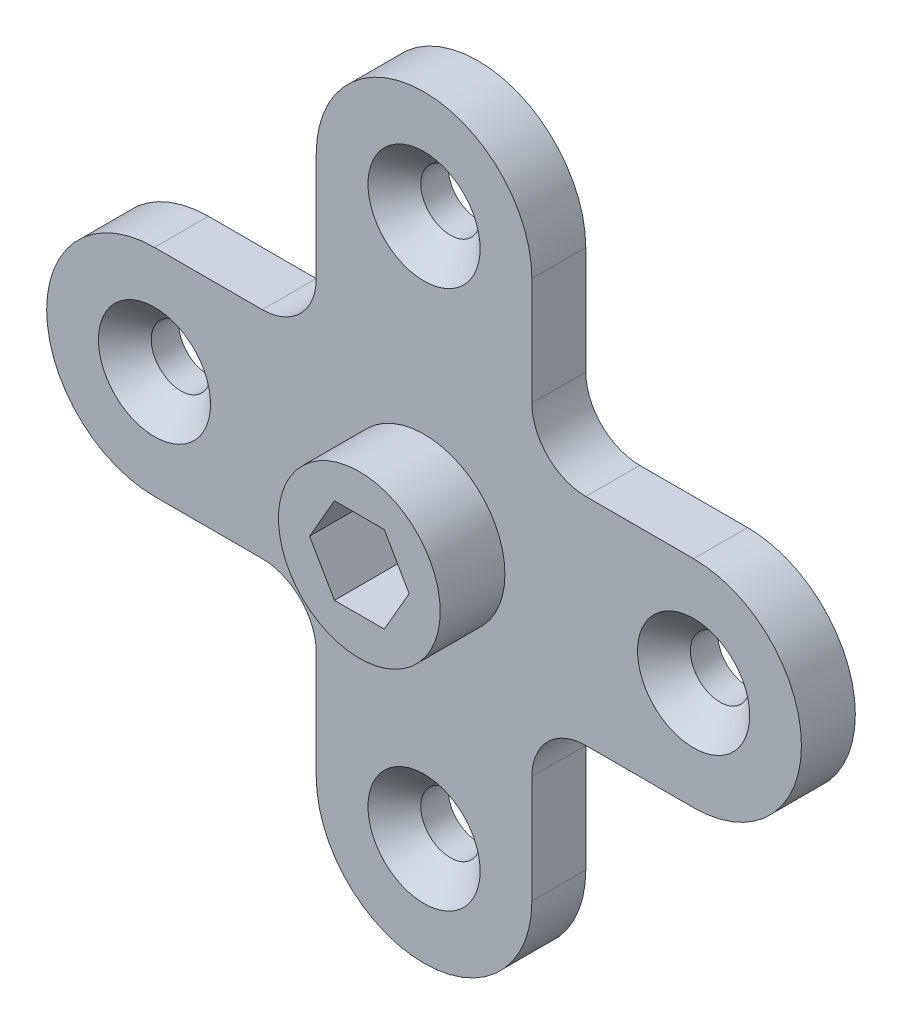
SolidWorks part; units mm, degrees
ref_plane "前基準面" through (0, 0, 0) normal (0, 0, 1) x (1, 0, 0)
ref_plane "上基準面" through (0, 0, 0) normal (0, 1, 0) x (1, 0, 0)
ref_plane "右基準面" through (0, 0, 0) normal (1, 0, 0) x (0, 0, -1)
sketch "草圖1" plane through (0, 0, 0) normal (0, 0, 1) x (1, 0, 0)
  line L0 (-25, 0) -> (25, 0) construction
  line L1 (0, 25) -> (0, -25) construction
  line L2 (0, 25) -> (0, -25) construction
  line L3 (10, 25) -> (10, 10)
  line L4 (-10, 25) -> (-10, 10)
  line L5 (-25, 0) -> (25, 0) construction
  line L6 (-25, 10) -> (-10, 10)
  line L7 (-25, -10) -> (-10, -10)
  line L8 (-10, -10) -> (-10, -25)
  line L9 (10, -10) -> (10, -25)
  line L10 (10, -10) -> (25, -10)
  line L11 (10, 10) -> (25, 10)
  arc A0 (10, 25) -> (-10, 25) centre (0, 25) ccw
  arc A1 (-10, -25) -> (10, -25) centre (0, -25) ccw
  arc A2 (-25, 10) -> (-25, -10) centre (-25, 0) ccw
  arc A3 (25, -10) -> (25, 10) centre (25, 0) ccw
  circle A4 centre (-25, 0) radius 2.5 construction
  circle A5 centre (25, 0) radius 2.5 construction
  circle A6 centre (0, 25) radius 2.5 construction
  circle A7 centre (0, -25) radius 2.5 construction
  point P4 (0, 0)
  point P6 (0, 0)
  point P7 (0, 0)
  point P12 (0, 0)
  point P26 (0, 25)
  point P27 (-25, 0)
  point P28 (0, -25)
  point P29 (25, 0)
  dimension "D3" = 10
  dimension "D4" = 10
  dimension "D5" = 5
  dimension "D1" = 50
  dimension "D2" = 50
extrude "填料-伸長1" add sketch "草圖1" along normal mid plane 5
sketch "草圖2" plane through (0, 0, 2.5) normal (0, 0, 1) x (1, 0, 0)
  point P0 (0, 25)
  point P1 (-25, 0)
  point P3 (0, -25)
  point P5 (25, 0)
hole_wizard "M5 錐坑平頭螺釘的錐孔1" positions "3D草圖2" profile "草圖6" countersink size "M5" standard "ISO" end condition through all
sketch3d "3D草圖2"
  point P0 (0, 25, 2.5)
  point P3 (0, -25, 2.5)
  point P6 (25, 0, 2.5)
  point P9 (-25, 0, 2.5)
sketch "草圖6" plane through (0, 25, 2.5) normal (1, 0, 0) x (0, -1, 0)
  line L0 (0, 0) -> (0, 5)
  line L1 (0, 5) -> (2.75, 5)
  line L2 (2.75, 5) -> (2.75, 2.45)
  line L3 (2.75, 2.45) -> (5.2, 0)
  line L5 (5.2, 0) -> (0, 0)
  line L6 (-2.75, 2.45) -> (-5.2, 0) construction
  line L11 (0, -6.35) -> (0, 107.95) construction
  dimension "貫穿孔直徑" = 5.5
  dimension "貫穿孔深度" = 5
  dimension "近端錐孔直徑" = 10.4
  dimension "近端錐孔角度" = 90
fillet "圓角1" radius 5 4 edges at (-10, -10, 0) (-10, 10, 0) (10, 10, 0) (10, -10, 0)
sketch "草圖10" plane through (0, 0, -2.5) normal (0, 0, -1) x (-1, 0, 0)
  line L0 (0, 0) -> (0, 9.7359) construction
  line L1 (0, 9.7359) -> (8.944, 0) construction
  line L2 (8.944, 0) -> (-5.6831, 0) construction
  point P6 (0, 0)
hole_wizard "M5 錐坑平頭螺釘的錐孔3" positions "3D草圖7" profile "草圖13" countersink size "M5" standard "ISO" end condition through all
sketch3d "3D草圖7"
  point P0 (0, 0, -2.5)
sketch "草圖13" plane through (0, 0, -2.5) normal (1, 0, 0) x (0, 1, 0)
  line L0 (0, 0) -> (0, 5)
  line L1 (0, 5) -> (2.75, 5)
  line L2 (2.75, 5) -> (2.75, 2.45)
  line L3 (2.75, 2.45) -> (5.2, 0)
  line L5 (5.2, 0) -> (0, 0)
  line L6 (-2.75, 2.45) -> (-5.2, 0) construction
  line L11 (0, -6.35) -> (0, 107.95) construction
  dimension "貫穿孔直徑" = 5.5
  dimension "貫穿孔深度" = 5
  dimension "近端錐孔直徑" = 10.4
  dimension "近端錐孔角度" = 90
sketch "草圖14" plane through (0, 0, 2.5) normal (0, 0, 1) x (1, 0, 0)
  line L1 (2.3094, 4) -> (-2.3094, 4)
  line L2 (-2.3094, 4) -> (-4.6188, 0)
  line L3 (-4.6188, 0) -> (-2.3094, -4)
  line L4 (-2.3094, -4) -> (2.3094, -4)
  line L5 (2.3094, -4) -> (4.6188, 0)
  line L6 (4.6188, 0) -> (2.3094, 4)
  circle A0 centre (0, 0) radius 7.5
  circle A1 centre (0, 0) radius 4 construction
  dimension "D1" = 8
  dimension "D2" = 15
extrude "填料-伸長2" add sketch "草圖14" along normal blind 6
